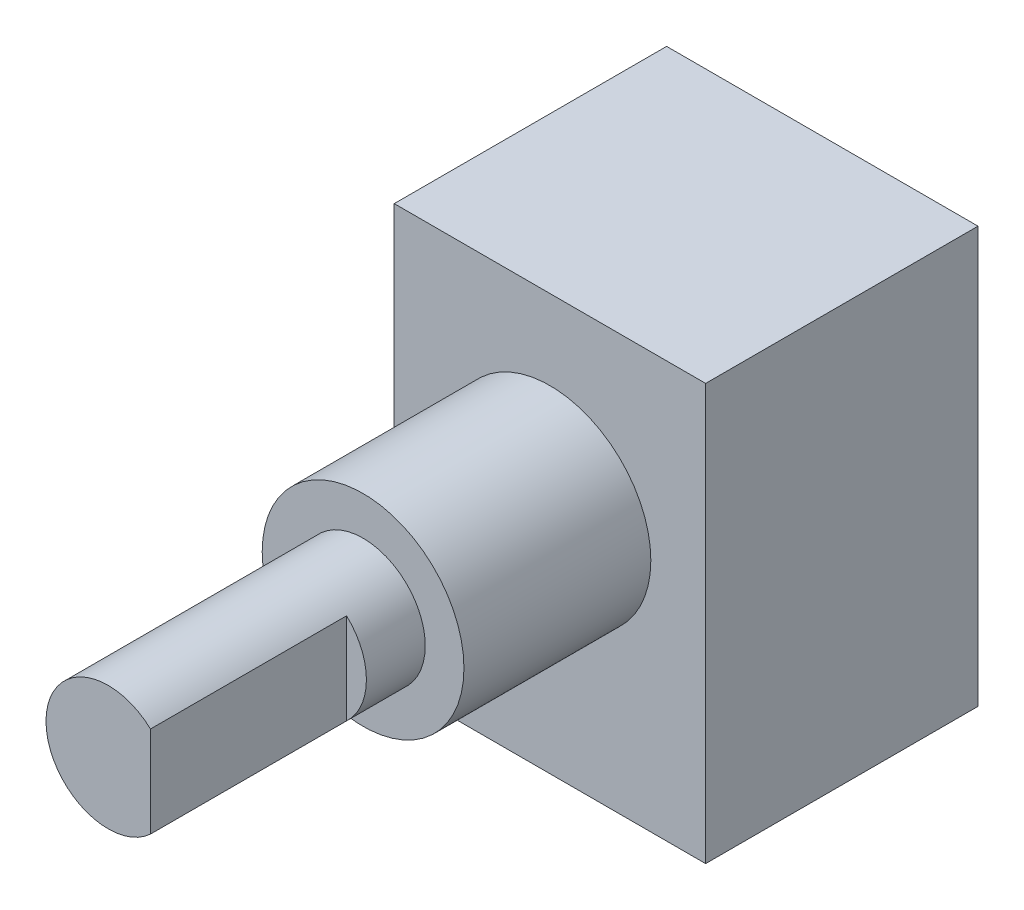
SolidWorks part; units mm, degrees
ref_plane "Front Plane" through (0, 0, 0) normal (0, 0, 1) x (1, 0, 0)
ref_plane "Top Plane" through (0, 0, 0) normal (0, 1, 0) x (1, 0, 0)
ref_plane "Right Plane" through (0, 0, 0) normal (1, 0, 0) x (0, 0, -1)
sketch "Sketch2" plane through (0, 0, 0) normal (0, 0, 1) x (1, 0, 0)
  line L1 (0, 0) -> (15.88, 0)
  line L2 (0, 0) -> (0, 21.21)
  line L3 (0, 21.21) -> (15.88, 21.21)
  line L4 (15.88, 0) -> (15.88, 21.21)
  dimension "D1" = 15.88
  dimension "D2" = 21.21
extrude "Boss-Extrude1" add sketch "Sketch2" along normal blind 13.89
sketch "Sketch3" plane through (0, 0, 13.89) normal (0, 0, 1) x (1, 0, 0)
  line L0 (0, 0) -> (15.88, 0) construction
  line L1 (0, 21.21) -> (0, 0) construction
  circle A0 centre (7.94, 12) radius 5.145
  dimension "D1" = 10.29
  dimension "D2" = 12
  dimension "D3" = 7.94
extrude "Boss-Extrude2" add sketch "Sketch3" along normal blind 9.53
sketch "Sketch4" plane through (0, 0, 23.42) normal (0, 0, 1) x (1, 0, 0)
  circle A1 centre (7.94, 12) radius 3.17
  dimension "D1" = 6.34
extrude "Boss-Extrude3" add sketch "Sketch4" along normal offset from surface (13 mm away) 22.53 up to face at (13.085, 12, 13.89) offset beyond the face yes
sketch "Sketch5" plane through (0, 0, 36.42) normal (0, 0, 1) x (1, 0, 0)
  line L0 (10.099, 14.3279) -> (10.099, 9.6721)
  arc A0 (10.099, 9.6721) -> (10.099, 14.3279) centre (7.94, 12) ccw
  dimension "D1" = 6.35
  dimension "D2" = 2.159
extrude "Cut-Extrude1" cut sketch "Sketch5" against normal blind 10
